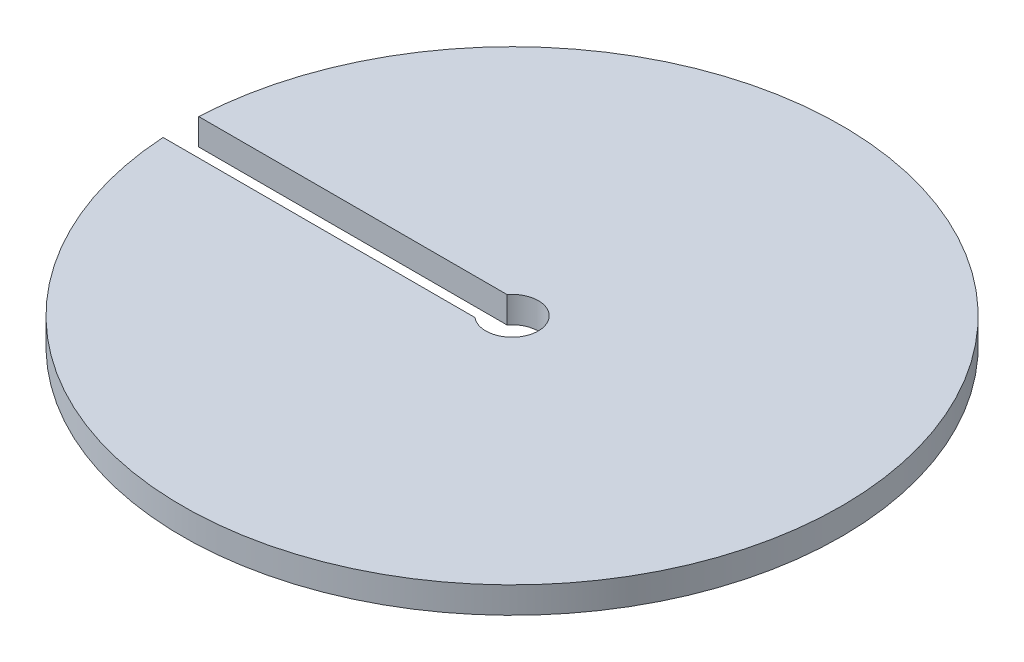
SolidWorks part; units mm, degrees
ref_plane "Front Plane" through (0, 0, 0) normal (0, 0, 1) x (1, 0, 0)
ref_plane "Top Plane" through (0, 0, 0) normal (0, 1, 0) x (1, 0, 0)
ref_plane "Right Plane" through (0, 0, 0) normal (1, 0, 0) x (0, 0, -1)
sketch "Sketch1" plane through (0, 0, 0) normal (0, 1, 0) x (1, 0, 0)
  line L0 (-6.4391, -7.5984) -> (-124.7688, -7.5984)
  line L1 (-7.9314, 6.0241) -> (-124.8548, 6.0241)
  arc A0 (-124.7688, -7.5984) -> (-124.8548, 6.0241) centre (0, 0) ccw
  arc A1 (-6.4391, -7.5984) -> (-7.9314, 6.0241) centre (0, 0) ccw
  point P8 (0, 0)
  point P9 (0, 0)
  dimension "D1" = 250
extrude "Boss-Extrude2" add sketch "Sketch1" along normal mid plane 10
